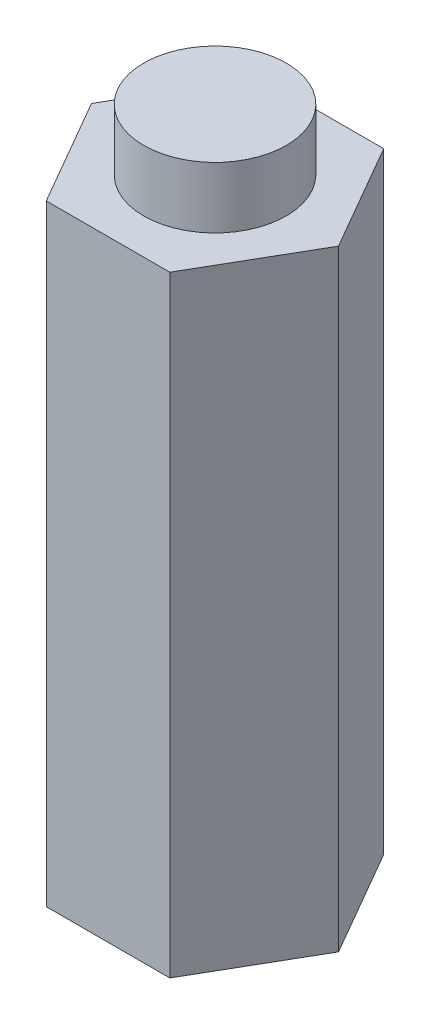
SolidWorks part; units mm, degrees
ref_plane "Front Plane" through (0, 0, 0) normal (0, 0, 1) x (1, 0, 0)
ref_plane "Top Plane" through (0, 0, 0) normal (0, 1, 0) x (1, 0, 0)
ref_plane "Right Plane" through (0, 0, 0) normal (1, 0, 0) x (0, 0, -1)
sketch "Sketch2" plane through (0, 0, 0) normal (0, 1, 0) x (1, 0, 0)
  line L1 (-12.1244, 0) -> (-6.0622, -10.5)
  line L2 (-6.0622, -10.5) -> (6.0622, -10.5)
  line L3 (6.0622, -10.5) -> (12.1244, 0)
  line L4 (12.1244, 0) -> (6.0622, 10.5)
  line L5 (6.0622, 10.5) -> (-6.0622, 10.5)
  line L6 (-6.0622, 10.5) -> (-12.1244, 0)
  circle A1 centre (0, 0) radius 10.5 construction
  dimension "D2" = 21
extrude "Boss-Extrude2" add sketch "Sketch2" along normal blind 60
sketch "Sketch3" plane through (0, 60, 0) normal (0, 1, 0) x (1, 0, 0)
  circle A0 centre (0, 0) radius 7
extrude "Boss-Extrude3" add sketch "Sketch3" along normal blind 6
